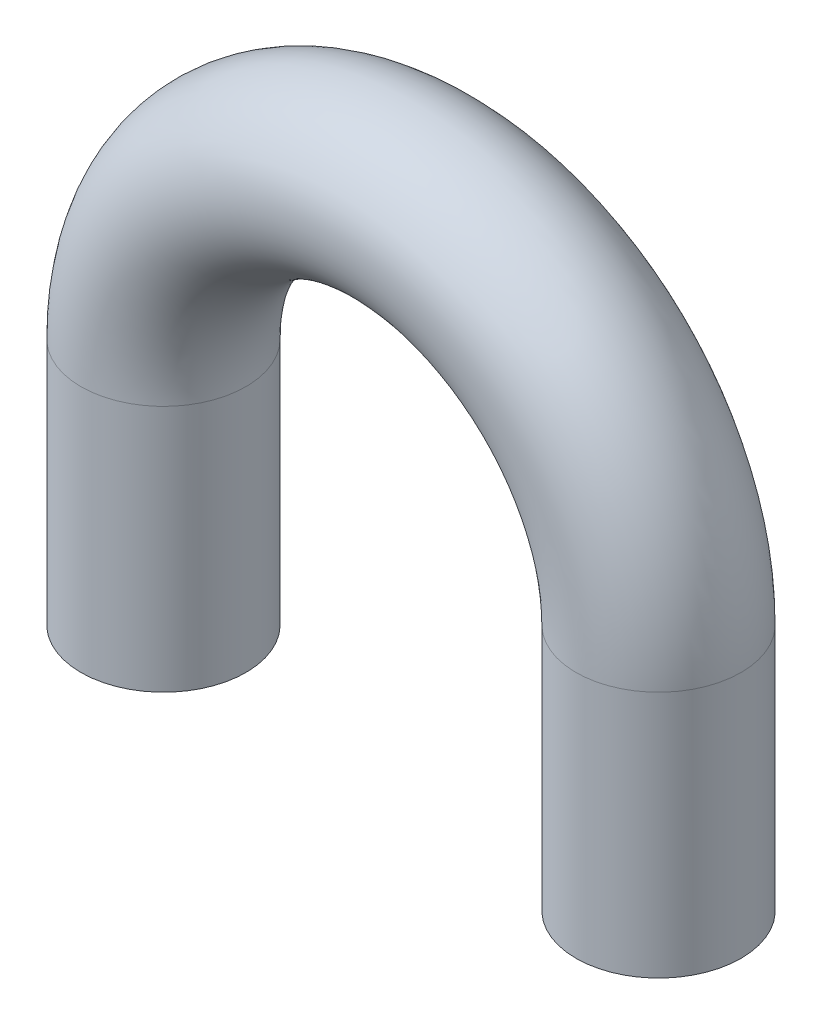
SolidWorks part; units mm, degrees
material "Bronze d'aluminium"
ref_plane "Face" through (0, 0, 0) normal (0, 0, 1) x (1, 0, 0)
ref_plane "Dessus" through (0, 0, 0) normal (0, 1, 0) x (1, 0, 0)
ref_plane "Droite" through (0, 0, 0) normal (1, 0, 0) x (0, 0, -1)
sketch "Esquisse1" plane through (0, 0, 0) normal (0, 0, 1) x (1, 0, 0)
  line L0 (-3, 3) -> (-3, 0)
  line L1 (3, 3) -> (3, 0)
  arc A0 (3, 3) -> (-3, 3) centre (0, 3) ccw
  dimension "D1" = 3
  dimension "D2" = 3
sketch "Esquisse3" plane through (0, 0, 0) normal (0, 1, 0) x (1, 0, 0)
  circle A0 centre (3, 0) radius 1
  dimension "D1" = 2
sweep "Balayage1" add profiles "Esquisse3" path "Esquisse1"
move or copy body "Body-Move/Copy1" [suppressed] bodies to move or copy 101 parameters "D1"=0, "D2"=0, "D3"=0
move or copy body "Body-Move/Copy2" [suppressed] bodies to move or copy 102 parameters "D1"=0, "D2"=0, "D3"=0
move or copy body "Body-Move/Copy3" [suppressed] bodies to move or copy 103 parameters "D1"=0, "D2"=0, "D3"=0
